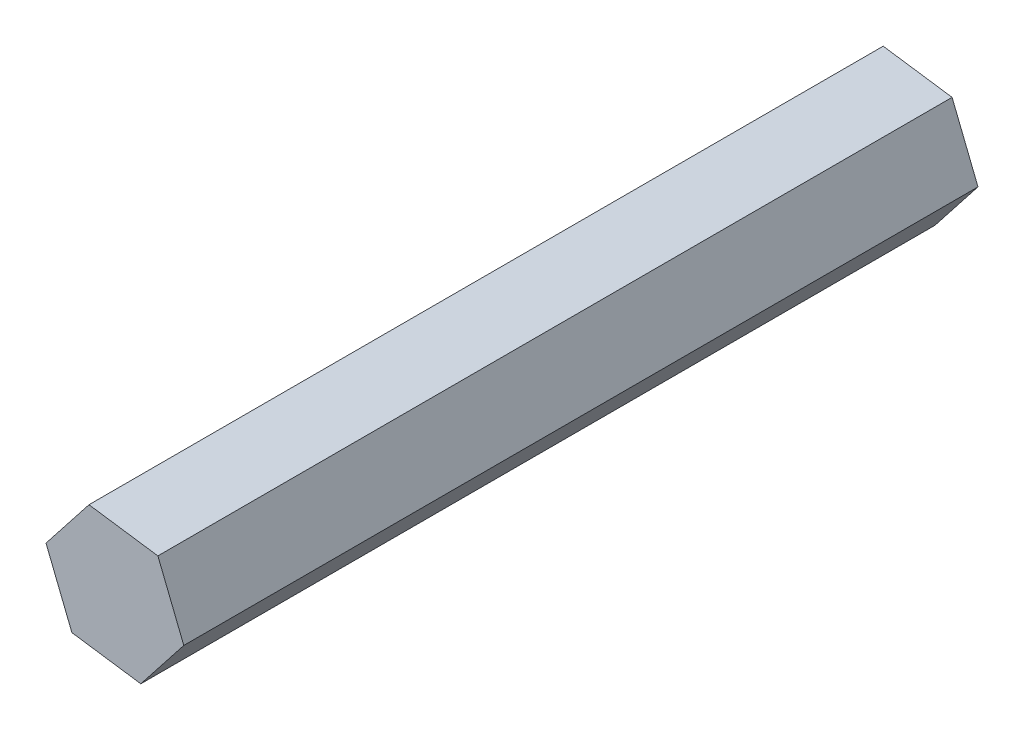
SolidWorks part; units mm, degrees
ref_plane "Front Plane" through (0, 0, 0) normal (0, 0, 1) x (1, 0, 0)
ref_plane "Top Plane" through (0, 0, 0) normal (0, 1, 0) x (1, 0, 0)
ref_plane "Right Plane" through (0, 0, 0) normal (1, 0, 0) x (0, 0, -1)
sketch "Sketch1" plane through (0, 0, 0) normal (0, 0, 1) x (1, 0, 0)
  line L1 (4.5287, 5.7666) -> (-2.7297, 6.8053)
  line L2 (-2.7297, 6.8053) -> (-7.2584, 1.0387)
  line L3 (-7.2584, 1.0387) -> (-4.5287, -5.7666)
  line L4 (-4.5287, -5.7666) -> (2.7297, -6.8053)
  line L5 (2.7297, -6.8053) -> (7.2584, -1.0387)
  line L6 (7.2584, -1.0387) -> (4.5287, 5.7666)
  circle A0 centre (0, 0) radius 6.35 construction
  dimension "D1" = 12.7
extrude "Boss-Extrude1" add sketch "Sketch1" along normal blind 83.668
